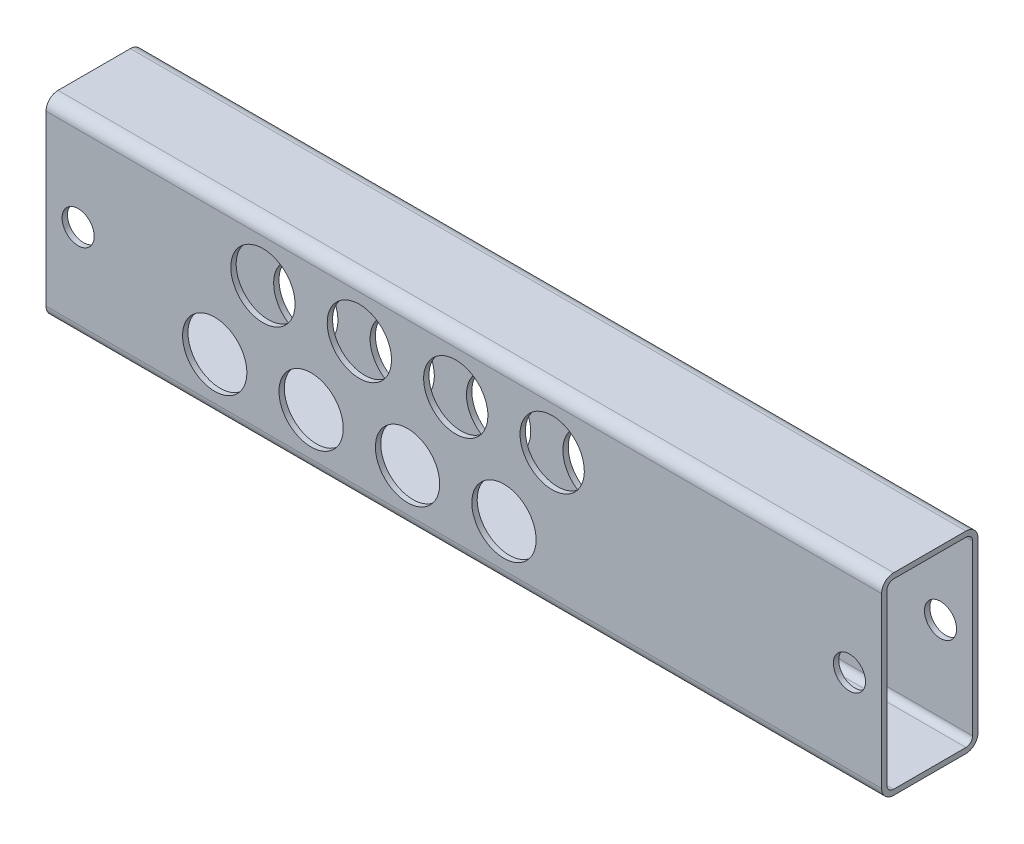
SolidWorks part; units mm, degrees
material "Plain Carbon Steel"
ref_plane "Front Plane" through (0, 0, 0) normal (0, 0, 1) x (1, 0, 0)
ref_plane "Top Plane" through (0, 0, 0) normal (0, 1, 0) x (1, 0, 0)
ref_plane "Right Plane" through (0, 0, 0) normal (1, 0, 0) x (0, 0, -1)
sketch "Sketch1" plane through (0, 0, 0) normal (0, 0, 1) x (1, 0, 0)
  line L0 (107.95, 0) -> (-222.25, 0)
  line L1 (-57.15, 0) -> (-57.15, 64.5545) construction
  line L2 (38.1, 0) -> (38.1, 33.5084) construction
  dimension "D1" = 57.15
  dimension "D2" = 330.2
  dimension "D3" = 38.1
other "Structural Member1"
ref_plane "Plane1" through (107.95, 0, 0) normal (-1, 0, 0) x (0, 0, 1)
sketch "Sketch13" plane through (107.95, 0, 0) normal (-1, 0, 0) x (0, 0, 1)
  line L0 (-14.2875, -35.9842) -> (14.2875, -35.9842)
  line L1 (-16.9342, -33.3375) -> (-16.9342, 33.3375)
  line L2 (14.2875, 35.9842) -> (-14.2875, 35.9842)
  line L3 (16.9342, 33.3375) -> (16.9342, -33.3375)
  line L4 (-14.2875, -38.1) -> (14.2875, -38.1)
  line L5 (-19.05, -33.3375) -> (-19.05, 33.3375)
  line L6 (14.2875, 38.1) -> (-14.2875, 38.1)
  line L7 (19.05, 33.3375) -> (19.05, -33.3375)
  line L8 (0, 0) -> (19.05, 0) construction
  line L9 (0, 0) -> (0, 38.1) construction
  arc A0 (19.05, 33.3375) -> (14.2875, 38.1) centre (14.2875, 33.3375) ccw
  arc A1 (14.2875, -38.1) -> (19.05, -33.3375) centre (14.2875, -33.3375) ccw
  arc A2 (-19.05, -33.3375) -> (-14.2875, -38.1) centre (-14.2875, -33.3375) ccw
  arc A3 (-14.2875, 38.1) -> (-19.05, 33.3375) centre (-14.2875, 33.3375) ccw
  arc A4 (-14.2875, 35.9842) -> (-16.9342, 33.3375) centre (-14.2875, 33.3375) ccw
  arc A5 (16.9342, 33.3375) -> (14.2875, 35.9842) centre (14.2875, 33.3375) ccw
  arc A6 (14.2875, -35.9842) -> (16.9342, -33.3375) centre (14.2875, -33.3375) ccw
  arc A7 (-16.9342, -33.3375) -> (-14.2875, -35.9842) centre (-14.2875, -33.3375) ccw
  point P3 (0, -38.1)
  point P4 (-19.05, 0)
  point P5 (0, 0)
  point P6 (19.05, -38.1)
  point P7 (-19.05, -38.1)
  point P8 (-19.05, 38.1)
  point P33 (0, 0)
  point P35 (19.05, 38.1)
  point P36 (19.05, 0)
  point P37 (0, 38.1)
  dimension "D1" = 4.7625
  dimension "Thickness" = 2.1158
  dimension "V_leg" = 76.2
  dimension "H_leg" = 38.1
sketch "Sketch15" plane through (0, 0, -19.05) normal (0, 0, -1) x (-1, 0, 0)
  line L0 (-107.95, 0) -> (222.25, 0) construction
  line L1 (57.15, 0) -> (57.15, 64.1416) construction
  circle A0 centre (-95.25, 0) radius 6.35
  circle A1 centre (209.55, 0) radius 6.35
  dimension "D2" = 12.7
  dimension "D1" = 304.8
extrude "Cut-Extrude1" cut sketch "Sketch15" against normal through all
sketch "Sketch16" plane through (0, 0, -19.05) normal (0, 0, -1) x (-1, 0, 0)
  line L0 (-107.95, 0) -> (222.25, 0) construction
  line L2 (30.8549, -0.5168) -> (32.6451, 0.5168) construction
  line L3 (22.225, 16.4978) -> (22.225, 0) construction
  line L4 (41.275, -16.4978) -> (41.275, 0) construction
  line L5 (222.25, 33.3375) -> (222.25, -33.3375) construction
  line L6 (-107.95, 33.3375) -> (-107.95, -33.3375) construction
  circle A0 centre (22.225, 16.4978) radius 12.7
  circle A1 centre (41.275, -16.4978) radius 12.7
  point P11 (31.75, 0)
  dimension "D4" = 25.4
  dimension "D1" = 30
  dimension "D2" = 19.05
  dimension "D3" = 139.7
extrude "Cut-Extrude2" cut sketch "Sketch16" against normal through all
pattern_linear "LPattern1" count 4 spacing 38.1 along (-1, 0, 0) of "Cut-Extrude2"
